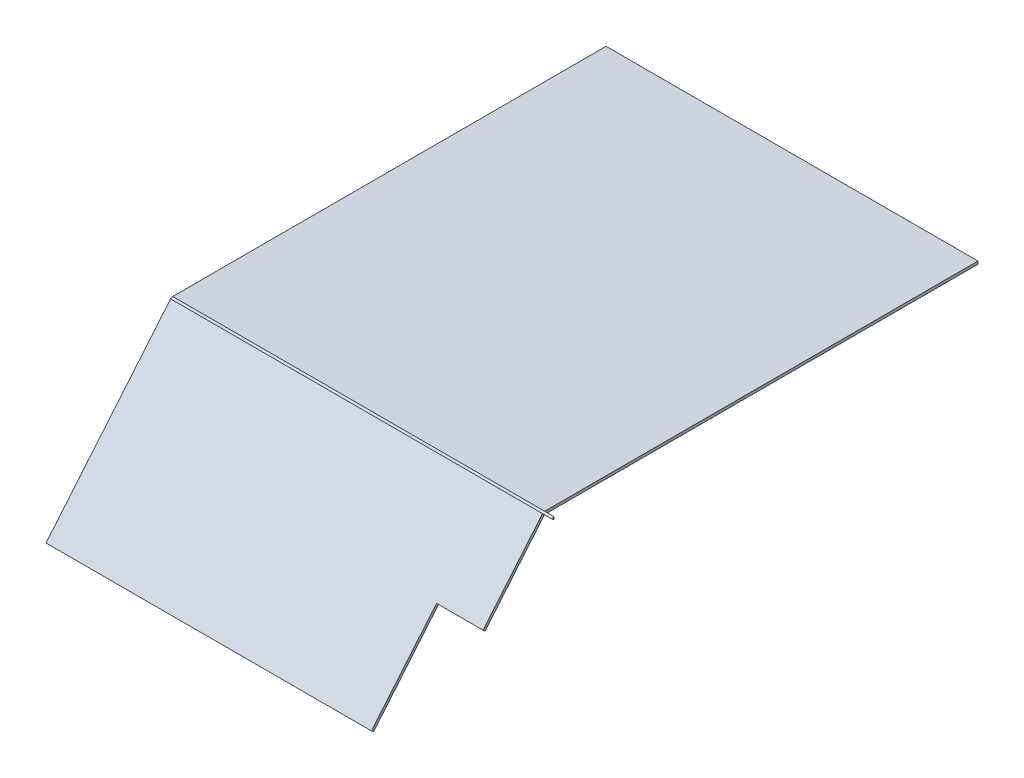
SolidWorks part; units mm, degrees
ref_plane "Front Plane" through (0, 0, 0) normal (0, 0, 1) x (1, 0, 0)
ref_plane "Top Plane" through (0, 0, 0) normal (0, 1, 0) x (1, 0, 0)
ref_plane "Right Plane" through (0, 0, 0) normal (1, 0, 0) x (0, 0, -1)
sketch3d "3DSketch1"
  line L0 (-317.9336, 130.2944, 321.7915) -> (-317.9336, 130.2944, 787.8131) construction
  line L1 (82.0664, 130.2944, 321.7915) -> (-317.9336, 130.2944, 321.7915) construction
  line L2 (82.0664, 130.2944, 787.8131) -> (82.0664, 130.2944, 321.7915) construction
  line L3 (-317.9336, 130.2944, 321.7915) -> (-317.9336, 130.2944, 787.8131)
  line L4 (82.0664, 130.2944, 321.7915) -> (-317.9336, 130.2944, 321.7915)
  line L5 (82.0664, 130.2944, 787.8131) -> (82.0664, 130.2944, 321.7915)
  line L6 (82.0664, 130.2944, 787.8131) -> (-317.9336, 130.2944, 787.8131)
  line L7 (82.0664, 130.2944, 787.8131) -> (82.0664, 53.7073, 851.7915) construction
  line L8 (82.0664, 53.7073, 851.7915) -> (32.0664, 53.7073, 851.7915) construction
  line L9 (32.0664, 53.7073, 851.7915) -> (32.0664, -30.088, 921.7915) construction
  line L10 (32.0664, -30.088, 921.7915) -> (-317.9336, -30.088, 921.7915) construction
  line L11 (-317.9336, -30.088, 921.7915) -> (-317.9336, 130.2944, 787.8131) construction
  line L12 (82.0664, 130.2944, 787.8131) -> (82.0664, 53.7073, 851.7915)
  line L13 (82.0664, 53.7073, 851.7915) -> (32.0664, 53.7073, 851.7915)
  line L14 (32.0664, 53.7073, 851.7915) -> (32.0664, -30.088, 921.7915)
  line L15 (32.0664, -30.088, 921.7915) -> (-317.9336, -30.088, 921.7915)
  line L16 (-317.9336, -30.088, 921.7915) -> (-317.9336, 130.2944, 787.8131)
extrude "Boss-Extrude1" add sketch "3DSketch1" along a picked direction on the side against the normal blind 3 contours L6 L3 L4 L5
ref_plane "Plane1" through (0, 441.1716, 528.116) normal (0, 0.6411, 0.7675) x (1, 0, 0)
sketch "Sketch2" plane through (0, 441.1716, 528.116) normal (0, 0.6411, 0.7675) x (1, 0, 0)
  line L0 (-317.9336, -614.057) -> (-317.9336, -405.0767) construction
  line L1 (-317.9336, -614.057) -> (-317.9336, -405.0767)
  line L2 (32.0664, -614.057) -> (-317.9336, -614.057) construction
  line L3 (32.0664, -614.057) -> (-317.9336, -614.057)
  line L4 (32.0664, -504.8707) -> (32.0664, -614.057) construction
  line L5 (32.0664, -504.8707) -> (32.0664, -614.057)
  line L6 (82.0664, -504.8707) -> (32.0664, -504.8707) construction
  line L7 (82.0664, -504.8707) -> (32.0664, -504.8707)
  line L8 (82.0664, -405.0767) -> (82.0664, -504.8707) construction
  line L9 (82.0664, -405.0767) -> (82.0664, -504.8707)
  line L10 (-317.9336, -405.0767) -> (82.0664, -405.0767)
extrude "Boss-Extrude3" add sketch "Sketch2" along normal blind 3 separate body
ref_plane "Plane2" through (-327.9336, 0, 0) normal (-1, 0, 0) x (0, 0, 1)
sketch "Sketch3" plane through (-327.9336, 0, 0) normal (-1, 0, 0) x (0, 0, 1)
  line L0 (787.8131, 130.2944) -> (787.8131, 133.2944)
  line L1 (787.8131, 133.2944) -> (790.1154, 132.2178)
  line L2 (790.1154, 132.2178) -> (787.8131, 130.2944)
extrude "Boss-Extrude4" add sketch "Sketch3" against normal blind 410 from surface at -10 starting at face at (-317.9336, 51.0649, 855.9535)
